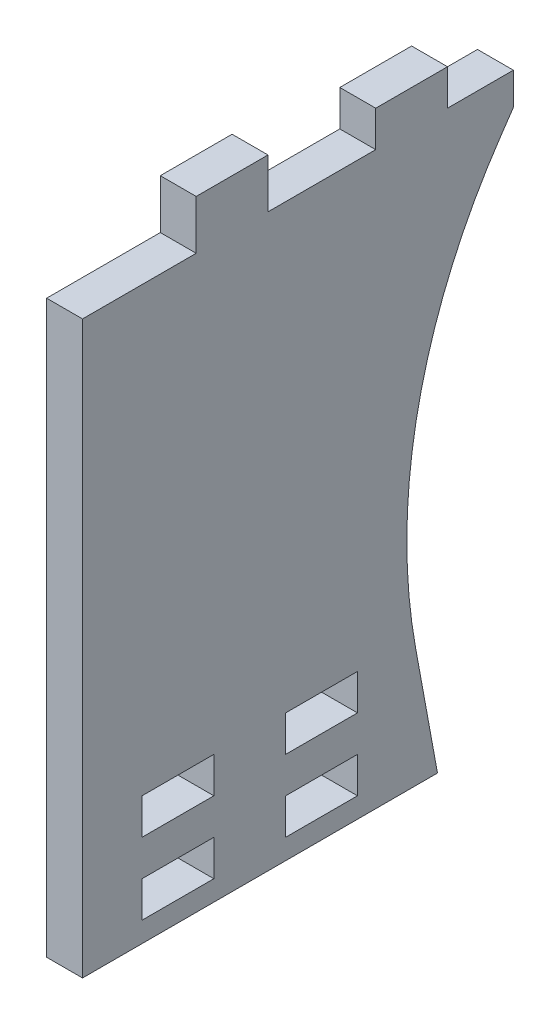
SolidWorks part; units mm, degrees
ref_plane "Front Plane" through (0, 0, 0) normal (0, 0, 1) x (1, 0, 0)
ref_plane "Top Plane" through (0, 0, 0) normal (0, 1, 0) x (1, 0, 0)
ref_plane "Right Plane" through (0, 0, 0) normal (1, 0, 0) x (0, 0, -1)
sketch "Sketch1" plane through (0, 0, 0) normal (1, 0, 0) x (0, 0, -1)
  line L0 (-19.8098, 10.4051) -> (-19.8098, -84.9804)
  line L1 (-19.8098, -84.9804) -> (39.508, -84.9804)
  line L2 (52.1902, 5.0084) -> (50.0237, 1.8309)
  line L3 (52.1902, 5.0084) -> (52.1902, 10.4051)
  line L4 (-19.8098, 10.4051) -> (-0.8158, 10.4051)
  line L5 (-0.8158, 10.4051) -> (-0.8158, 18.637)
  line L6 (-0.8158, 18.637) -> (11.1842, 18.637)
  line L7 (11.1842, 18.637) -> (11.1842, 10.4051)
  line L8 (11.1842, 10.4051) -> (29.1842, 10.4051)
  line L9 (29.1842, 10.4051) -> (29.1842, 16.4051)
  line L10 (29.1842, 16.4051) -> (41.1842, 16.4051)
  line L11 (41.1842, 16.4051) -> (41.1842, 10.4051)
  line L12 (41.1842, 10.4051) -> (52.1902, 10.4051)
  line L13 (2.1369, -75.5861) -> (14.1369, -75.5861) construction
  line L14 (-9.8631, -75.5861) -> (2.1369, -75.5861)
  line L15 (-9.8631, -75.5861) -> (-9.8631, -81.5861)
  line L16 (-9.8631, -81.5861) -> (2.1369, -81.5861)
  line L17 (2.1369, -75.5861) -> (2.1369, -81.5861)
  line L18 (14.1369, -75.5861) -> (26.1369, -75.5861)
  line L19 (14.1369, -75.5861) -> (14.1369, -81.5861)
  line L20 (14.1369, -81.5861) -> (26.1369, -81.5861)
  line L21 (26.1369, -75.5861) -> (26.1369, -81.5861)
  line L22 (2.1369, -63.5861) -> (14.1369, -63.5861) construction
  line L23 (-9.8631, -63.5861) -> (2.1369, -63.5861)
  line L24 (-9.8631, -63.5861) -> (-9.8631, -69.5861)
  line L25 (-9.8631, -69.5861) -> (2.1369, -69.5861)
  line L26 (2.1369, -63.5861) -> (2.1369, -69.5861)
  line L27 (14.1369, -63.5861) -> (26.1369, -63.5861)
  line L28 (14.1369, -63.5861) -> (14.1369, -69.5861)
  line L29 (14.1369, -69.5861) -> (26.1369, -69.5861)
  line L30 (26.1369, -63.5861) -> (26.1369, -69.5861)
  line L31 (-9.8631, -69.5861) -> (-9.8631, -75.5861) construction
  line L32 (-9.8631, -63.5861) -> (-19.8098, -63.5861) construction
  line L33 (35.8623, -65.1177) -> (39.508, -84.9804)
  line L34 (14.1369, -75.5861) -> (14.1369, 10.4051) construction
  arc A0 (50.0237, 1.8309) -> (35.8623, -65.1177) centre (124.3836, -48.8702) ccw
  dimension "D1" = 90
extrude "Boss-Extrude1" add sketch "Sketch1" along normal blind 6
